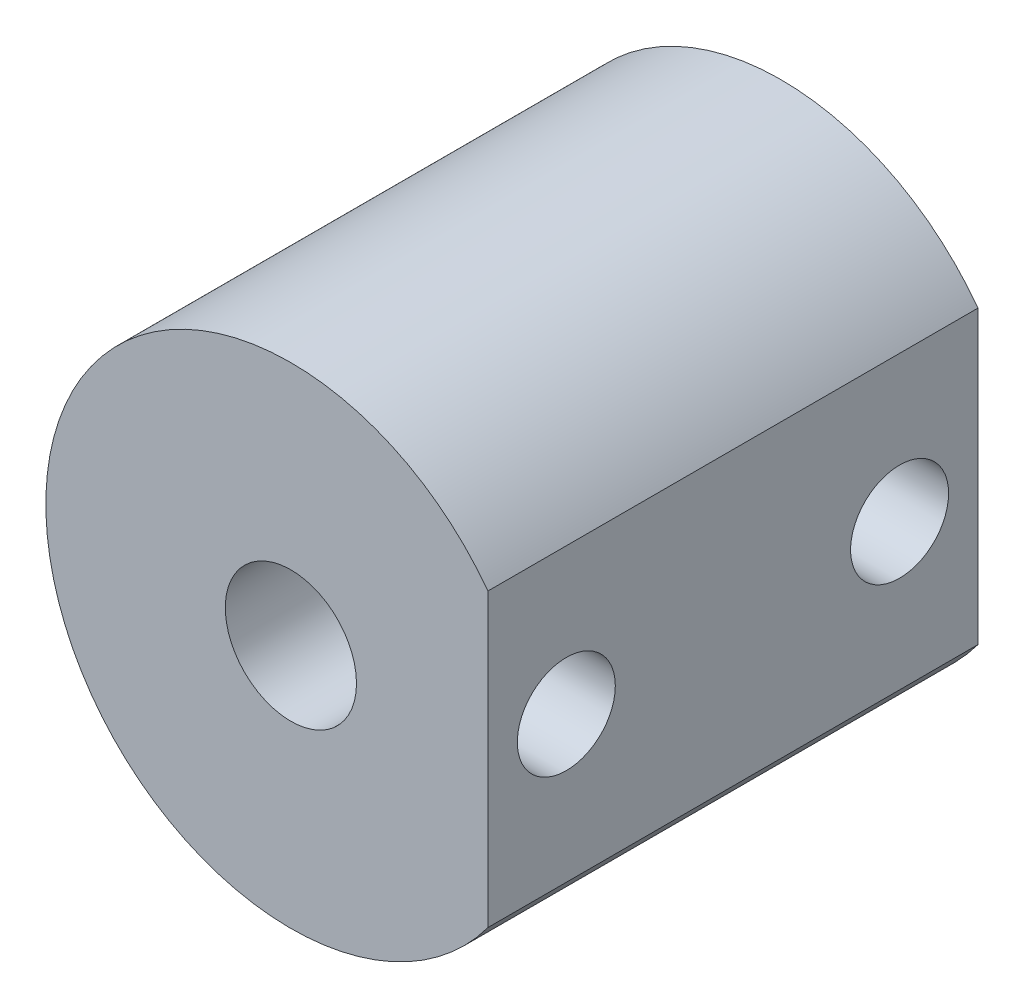
SolidWorks part; units mm, degrees
ref_plane "Front Plane" through (0, 0, 0) normal (0, 0, 1) x (1, 0, 0)
ref_plane "Top Plane" through (0, 0, 0) normal (0, 1, 0) x (1, 0, 0)
ref_plane "Right Plane" through (0, 0, 0) normal (1, 0, 0) x (0, 0, -1)
sketch "Sketch1" plane through (0, 0, 0) normal (0, 0, 1) x (1, 0, 0)
  circle A0 centre (0, 0) radius 6.35
  dimension "D1" = 12.7
extrude "Boss-Extrude1" add sketch "Sketch1" along normal blind 12.7
sketch "Sketch2" plane through (0, 0, 12.7) normal (0, 0, 1) x (1, 0, 0)
  circle A0 centre (0, 0) radius 1.7
  dimension "D1" = 3.4
extrude "Cut-Extrude1" cut sketch "Sketch2" against normal blind 6.35
sketch "Sketch3" plane through (0, 0, 0) normal (0, 0, -1) x (-1, 0, 0)
  line L1 (-2.5464, -1.4785) -> (0.0073, -2.9445)
  line L2 (0.0073, -2.9445) -> (2.5536, -1.4659)
  line L3 (2.5536, -1.4659) -> (2.5464, 1.4785)
  line L4 (2.5464, 1.4785) -> (-0.0073, 2.9445)
  line L5 (-0.0073, 2.9445) -> (-2.5536, 1.4659)
  line L6 (-2.5536, 1.4659) -> (-2.5464, -1.4785)
  circle A0 centre (0, 0) radius 2.55 construction
  dimension "D1" = 5.1
extrude "Cut-Extrude2" cut sketch "Sketch3" against normal blind 6.35
sketch "Sketch4" plane through (0, 0, 0) normal (0, 0, -1) x (-1, 0, 0)
  line L1 (-5.1052, -3.7762) -> (-8.2192, -3.7762)
  line L2 (-5.1052, -3.7762) -> (-5.1052, 4.1225)
  line L3 (-5.1052, 4.1225) -> (-8.2192, 4.1225)
  line L4 (-8.2192, -3.7762) -> (-8.2192, 4.1225)
  circle A0 centre (0, 0) radius 6.35 construction
extrude "Cut-Extrude3" cut sketch "Sketch4" against normal blind 14.224
sketch "Sketch5" plane through (5.1052, 0, 0) normal (1, 0, 0) x (0, 0, -1)
  line L0 (-12.7, 3.7762) -> (-12.7, -3.7762) construction
  line L1 (-12.7, 0) -> (0, 0) construction
  circle A0 centre (-10.668, 0) radius 1.27
  circle A1 centre (-2.032, 0) radius 1.27
  dimension "D1" = 2.54
  dimension "D2" = 2.54
  dimension "D3" = 2.032
  dimension "D4" = 2.032
extrude "Cut-Extrude4" cut sketch "Sketch5" against normal blind 3.81
